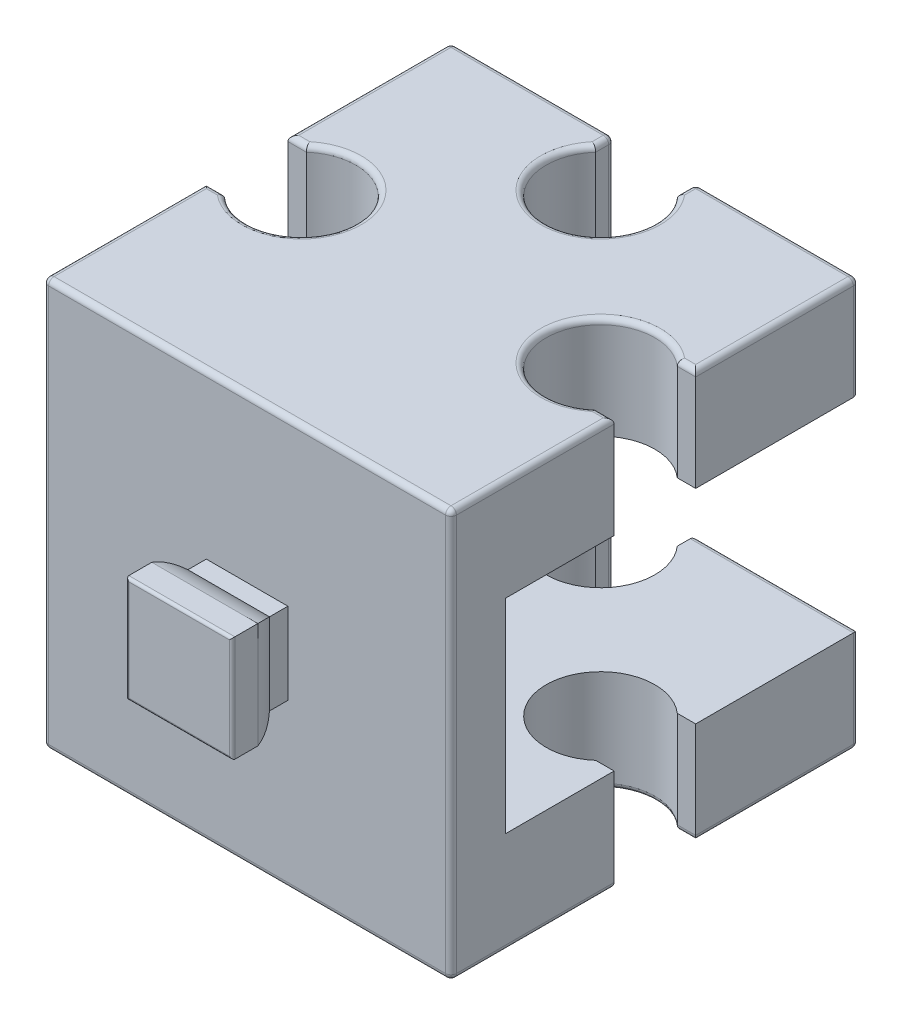
SolidWorks part; units mm, degrees
ref_plane "前视基准面" through (0, 0, 0) normal (0, 0, 1) x (1, 0, 0)
ref_plane "上视基准面" through (0, 0, 0) normal (0, 1, 0) x (1, 0, 0)
ref_plane "右视基准面" through (0, 0, 0) normal (1, 0, 0) x (0, 0, -1)
sketch "草图1" plane through (0, 0, 0) normal (0, 0, 1) x (1, 0, 0)
  line L1 (-7.5, -7.5) -> (7.5, -7.5)
  line L2 (-7.5, -7.5) -> (-7.5, 7.5)
  line L3 (-7.5, 7.5) -> (7.5, 7.5)
  line L4 (7.5, -7.5) -> (7.5, 7.5)
extrude "凸台-拉伸1" add sketch "草图1" against normal blind 15
sketch "草图2" plane through (0, 0, 0) normal (0, 1, 0) x (1, 0, 0)
  line L0 (-7.5, 0) -> (7.5, 0) construction
  line L1 (-1.5, 0) -> (1.5, 0)
  line L2 (-1.5, 0) -> (-1.5, -1)
  line L3 (-1.5, -1) -> (1.5, -1)
  line L4 (1.5, 0) -> (1.5, -1)
extrude "凸台-拉伸2" add sketch "草图2" along normal blind 1.5 and the other way blind 1.5
sketch "草图3" plane through (0, 0, 0) normal (0, 1, 0) x (1, 0, 0)
  line L1 (-1.95, -2.5) -> (1.95, -2.5)
  line L2 (-1.95, -2.5) -> (-1.95, -1.5556)
  line L3 (1.95, -2.5) -> (1.95, -1.5556)
  line L4 (-1.5, 0) -> (-1.5, -1) construction
  line L5 (-1.5, -0.6771) -> (1.5, -0.6771)
  arc A0 (-1.5, -0.6771) -> (-1.95, -1.5556) centre (0, -2) ccw
  arc A1 (1.95, -1.5556) -> (1.5, -0.6771) centre (0, -2) ccw
extrude "凸台-拉伸3" add sketch "草图3" along normal blind 3 and the other way blind 3
sketch "草图12" plane through (0, 0, 0) normal (1, 0, 0) x (0, 0, -1)
  line L0 (-2.5, 3) -> (-2.5, 1.95)
  line L1 (-2.5, 1.95) -> (-1.5556, 1.95)
  line L2 (-2.5, -1.95) -> (-1.5556, -1.95)
  line L5 (-2.5, -1.95) -> (-2.5, -3)
  line L6 (-2.5, 3) -> (-0.6771, 3)
  line L7 (-0.6771, 3) -> (-0.6771, 1.5)
  line L8 (-2.5, -3) -> (-0.6771, -3)
  line L9 (-0.6771, -3) -> (-0.6771, -1.5)
  arc A0 (-0.6771, 1.5) -> (-1.5556, 1.95) centre (-2, 0) ccw
  arc A1 (-1.5556, -1.95) -> (-0.6771, -1.5) centre (-2, 0) ccw
extrude "切除-拉伸7" cut sketch "草图12" against normal up to next and the other way up to next
fillet "圆角2" radius 0.1 4 edges at (-1.95, 0, 2.5) (0, -1.95, 2.5) (1.95, 0, 2.5) (0, 1.95, 2.5)
sketch "草图13" plane through (0, -7.5, 0) normal (0, -1, 0) x (-1, 0, 0)
  line L1 (7.5, 15) -> (-7.5, 15) construction
  line L2 (1.5, 15) -> (-1.5, 15)
  line L3 (1.5, 15) -> (1.5, 14.3229)
  line L5 (-1.5, 15) -> (-1.5, 14.3229)
  line L6 (7.5, 6) -> (7.5, 9)
  line L7 (7.5, 6) -> (6.8229, 6)
  line L8 (7.5, 9) -> (6.8229, 9)
  line L14 (-7.5, 9) -> (-7.5, 6)
  line L15 (-7.5, 9) -> (-6.8229, 9)
  line L16 (-7.5, 6) -> (-6.8229, 6)
  line L18 (-1.5, 0) -> (1.5, 0) [skipped]
  line L19 (-1.5, 0) -> (-1.5, 0.6771) [skipped]
  line L20 (1.5, 0) -> (1.5, 0.6771) [skipped]
  arc A0 (-1.5, 14.3229) -> (1.5, 14.3229) centre (0, 13) ccw
  arc A1 (6.8229, 9) -> (6.8229, 6) centre (5.5, 7.5) ccw
  arc A3 (-6.8229, 6) -> (-6.8229, 9) centre (-5.5, 7.5) ccw
  arc A4 (1.5, 0.6771) -> (-1.5, 0.6771) centre (0, 2) ccw [skipped]
  dimension "D1" = 4
extrude "切除-拉伸8" cut sketch "草图13" against normal through all
sketch "草图14" plane through (-7.5, 0, 0) normal (-1, 0, 0) x (0, 0, 1)
  line L0 (-15, 7.5) -> (-15, -7.5) construction
  line L1 (-15, 3.75) -> (-2, 3.75)
  line L2 (-15, 3.75) -> (-15, -3.75)
  line L3 (-15, -3.75) -> (-2, -3.75)
  line L4 (-2, 3.75) -> (-2, -3.75)
extrude "切除-拉伸9" cut sketch "草图14" against normal through all
fillet "圆角3" radius 0.2 46 edges at (1.5, -5.625, -15) (7.5, -5.625, -15) (4.5, -3.75, -15) (-7.5, -5.625, -15) (-1.5, -5.625, -15) (-4.5, -3.75, -15) (-1.5, 5.625, -15) (-7.5, 5.625, -15) (-4.5, 3.75, -15) (7.5, 5.625, -15) (1.5, 5.625, -15) (4.5, 3.75, -15) (7.5, 7.5, -3) (0, 7.5, 0) (-7.5, 7.5, -3) (-7.1614, 7.5, -6) (-3.5, 7.5, -7.5) (-7.1614, 7.5, -9) (-7.5, 7.5, -12) (-4.5, 7.5, -15) (-1.5, 7.5, -14.6614) (0, 7.5, -11) (1.5, 7.5, -14.6614) (4.5, 7.5, -15) (7.5, 7.5, -12) (7.1614, 7.5, -9) (3.5, 7.5, -7.5) (7.1614, 7.5, -6) (3.5, -7.5, -7.5) (7.1614, -7.5, -9) (7.5, -7.5, -12) (4.5, -7.5, -15) (1.5, -7.5, -14.6614) (0, -7.5, -11) (-1.5, -7.5, -14.6614) (-4.5, -7.5, -15) (-7.5, -7.5, -12) (-7.1614, -7.5, -9) (-3.5, -7.5, -7.5) (-7.1614, -7.5, -6) (-7.5, -7.5, -3) (0, -7.5, 0) (7.5, -7.5, -3) (7.1614, -7.5, -6) (-7.5, 0, 0) (7.5, 0, 0)
